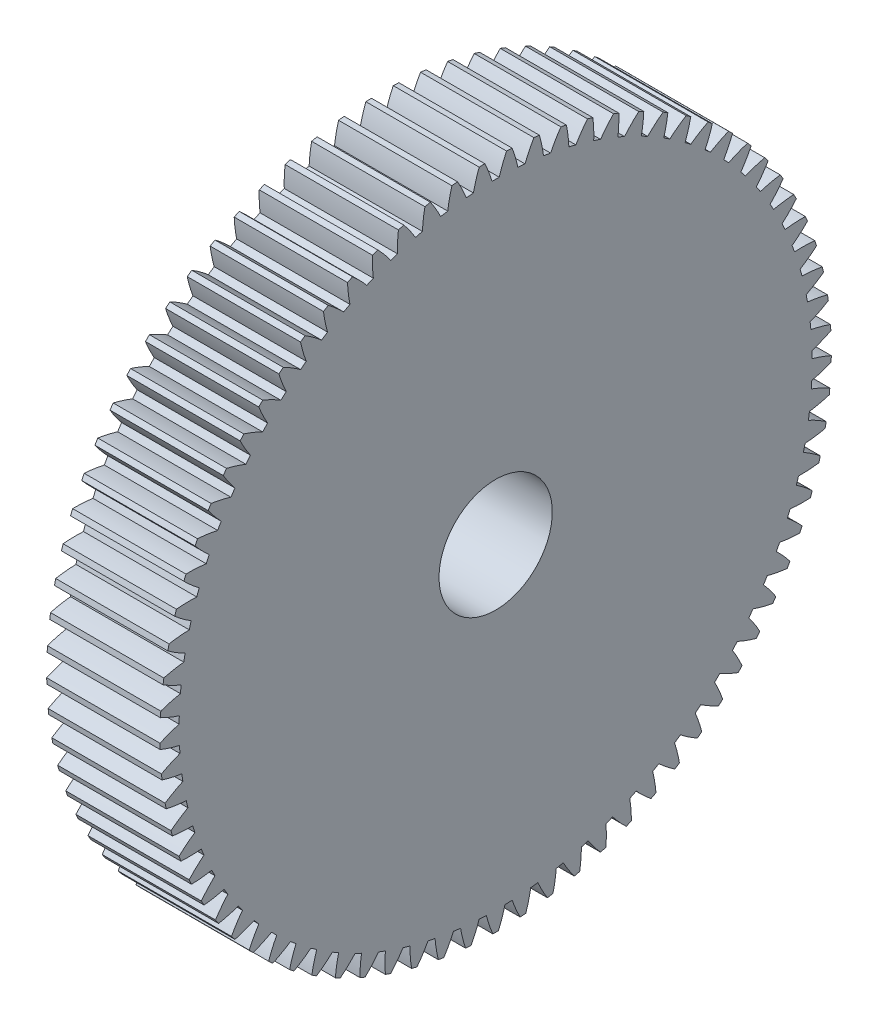
SolidWorks part; units mm, degrees
ref_plane "Plane1" through (0, 0, 0) normal (0, 0, 1) x (1, 0, 0)
ref_plane "Plane2" through (0, 0, 0) normal (0, 1, 0) x (1, 0, 0)
ref_plane "Plane3" through (0, 0, 0) normal (1, 0, 0) x (0, 0, -1)
sketch "HoldingSke" plane through (0, 0, 0) normal (0, 1, 0) x (1, 0, 0)
  line L0 (0, 0) -> (0.3749, -1.624)
  line L1 (-15, 0) -> (100, 0) construction
  line L2 (0, 0) -> (-2.1039, 2.3779)
  line L3 (0, 0) -> (-11.863, 4.5341)
  line L4 (0, 0) -> (1.9427, 8.4147)
  line L5 (0, 0) -> (-46.8476, -17.4728)
  line L6 (0, 0) -> (-6.6317, -4.4744)
  line L7 (-2.1039, 2.3779) -> (8.6586, 51.2059)
  line L8 (-76.2, 54.61) -> (-75.2, 54.61)
  line L9 (-71.009, 38.7566) -> (-53.1078, 45.2721)
  line L10 (-76.2, 71.12) -> (104.1128, 71.12)
  line L11 (0, 0) -> (-8, 0)
  line L12 (-76.2, 101.6) -> (-76.177, 101.6)
  line L13 (24.9733, 27.94) -> (52.9518, 28.4284)
  line L14 (24.9733, 27.94) -> (24.9743, 27.94)
  line L15 (24.9733, 27.94) -> (100.4006, 29.5858)
  line L16 (-63.627, -0.6) -> (-12.827, -0.6)
  circle A0 centre (0, 0) radius 4
  circle A1 centre (0, 0) radius 22.349
  circle A2 centre (0, 0) radius 37.5
  circle A3 centre (0, 0) radius 4
  dimension "MHD" = 44.698
  dimension "Hub_dia" = 75
  dimension "Bore" = 8
  dimension "MBD" = 8
  dimension "Num_teeth" = 77
  dimension "Pitch" = 1.6667
  dimension "Overall_len" = 50
  dimension "Show_teeth" = 77
  dimension "Thickness" = 8
  dimension "OAL" = 50.0001
  dimension "T_dim" = 1
  dimension "Ap" = 20
  dimension "H" = 19.05
  dimension "Pitch_radius" = 180.3128
  dimension "Width" = 8
  dimension "Backlash" = 0.023
  dimension "Addendum_fac" = 1
  dimension "Dedendum_fac" = 1.25
  dimension "Clearance_fac" = 0.25
  dimension "Dedendum_add" = 0.001
  dimension "Module" = 0.6
sketch "BasProSke" plane through (0, 0, 0) normal (0, 1, 0) x (1, 0, 0)
  line L0 (-10, 0) -> (60, 0) construction
  line L1 (0, 0) -> (0, 23.7)
  line L2 (0, 0) -> (8, 0)
  line L3 (8, 0) -> (8, 23.7)
  line L4 (8, 23.7) -> (0, 23.7)
  dimension "Thickness" = 8
  dimension "Diameter" = 47.4
revolve "Base-Revolve" add sketch "BasProSke" angle 360 about L0
sketch "TooCutSke" plane through (0, 0, 0) normal (1, 0, 0) x (0, 0, -1)
  line L1 (0, 0) -> (0, 107) construction
  line L2 (0, 0) -> (-0.5115, 23.0943) construction
  line L3 (0, 0) -> (-1.8841, 46.1535) construction
  line L4 (-0.5115, 23.0943) -> (-0.9421, 23.0768) construction
  arc A0 (0.2532, 22.3476) -> (-0.2532, 22.3476) centre (0, 0) ccw
  arc A1 (0.7818, 23.7125) -> (-0.7818, 23.7125) centre (0, 0) ccw
  circle A2 centre (0, 0) radius 23.1 construction
  circle A3 centre (0, 0) radius 21.7069 construction
  arc A4 (-0.2532, 22.3476) -> (-0.7818, 23.7125) centre (-9.107, 19.7041) ccw
  arc A5 (0.7818, 23.7125) -> (0.2532, 22.3476) centre (9.107, 19.7041) ccw
  dimension "Root_dia" = 44.698
  dimension "Overcut_dia" = 47.4508
  dimension "Pitch_dia" = 46.2
  dimension "Base_dia" = 43.4138
  dimension "Flank_rad" = 9.24
  dimension "Half_ang" = 2.338
  dimension "Half_CT" = 0.431
extrude "ToothCut" cut sketch "TooCutSke" along normal through all
fillet "Breaks" [suppressed] radius 0.012
fillet "RootFillets" [suppressed] radius 0.151
pattern_circular "TeethCuts" count 77 every 4.675 about axis through (-10, 0, 0) along (1, 0, 0) of "ToothCut", "RootFillets", "Breaks"
sketch "HubNeaOneSke" plane through (0, 0, 0) normal (-1, 0, 0) x (0, 0, 1)
  circle A0 centre (0, 0) radius 22.349
  dimension "Diameter" = 44.698
extrude "HubNearOne" [suppressed] add sketch "HubNeaOneSke" along normal blind 42.0001
sketch "HubNeaBotSke" plane through (0, 0, 0) normal (-1, 0, 0) x (0, 0, 1)
  circle A0 centre (0, 0) radius 22.349
  dimension "Diameter" = 44.698
extrude "HubNearBoth" [suppressed] add sketch "HubNeaBotSke" along normal blind 21
ref_plane "FarPln" through (8, 0, 0) normal (1, 0, 0) x (0, 0, -1)
sketch "HubFarSke" plane through (8, 0, 0) normal (1, 0, 0) x (0, 0, -1)
  circle A0 centre (0, 0) radius 22.349
  dimension "Diameter" = 44.698
extrude "HubFar" [suppressed] add sketch "HubFarSke" along normal blind 21
sketch "BorSke" plane through (0, 0, 0) normal (1, 0, 0) x (0, 0, -1)
  circle A0 centre (0, 0) radius 4
  dimension "Diameter" = 8
extrude "Bore" cut sketch "BorSke" along normal mid plane 100.0001
sketch "KeySke" plane through (0, 0, 0) normal (1, 0, 0) x (0, 0, -1)
  line L0 (-1, 0) -> (-1, 5)
  line L1 (-1, 5) -> (1, 5)
  line L2 (1, 5) -> (1, 0)
  line L3 (0, 0) -> (0, 34) construction
  line L4 (-1, 0) -> (1, 0)
  dimension "Offset" = 5
  dimension "Width" = 2
extrude "Keyway" [suppressed] cut sketch "KeySke" along normal mid plane 100.0001
pattern_circular "Keyway2" [suppressed] count 2 every 90 about axis through (-10, 0, 0) along (1, 0, 0)
equation "' \"Module@HoldingSke\" = 6.35"
equation "' \"Num_teeth@HoldingSke\" = 12"
equation "' \"Ap@HoldingSke\" =  20"
equation "' \"Ap@HoldingSke\" = 20"
equation "' \"Width@HoldingSke\" = 0.5 * 25.4"
equation "' \"Hub_dia@HoldingSke\"= 1 * 25.4"
equation "' \"Hub_dia@HoldingSke\" = 1 * 25.4"
equation "' \"Overall_len@HoldingSke\" = 1.0 * 25.4"
equation "' \"Bore@HoldingSke\" = 0.75 * 25.4"
equation "' \"T_dim@HoldingSke\" = 0.1 * 25.4"
equation "' \"Width@KeySke\" = 0.25 * 25.4"
equation "' \"Show_teeth@HoldingSke\" = 13"
equation "' \"Backlash@HoldingSke\" = 0.009 * 25.4"
equation "' \"Addendum_fac@HoldingSke\" = 1.0"
equation "' \"Dedendum_fac@HoldingSke\" = 1.25"
equation "' \"Dedendum_add@HoldingSke\" = 0.00005 * 25.4"
equation "' \"Clearance_fac@HoldingSke\" = 0.25"
equation "\"Pitch@HoldingSke\" = 1 / \"Module@HoldingSke\""
equation "\"Overcut_dia@TooCutSke\" = (\"Num_teeth@HoldingSke\" + 2 * \"Addendum_fac@HoldingSke\") / \"Pitch@HoldingSke\" + 0.002 * 25.4"
equation "\"Pitch_dia@TooCutSke\" = \"Num_teeth@HoldingSke\" / \"Pitch@HoldingSke\""
equation "\"Base_dia@TooCutSke\" = \"Num_teeth@HoldingSke\" / \"Pitch@HoldingSke\" * cos((\"Ap@HoldingSke\"  * 3.14159265 / 180))"
equation "\"Root_dia@TooCutSke\" = (\"Num_teeth@HoldingSke\" + 2) / \"Pitch@HoldingSke\" - 2 * (\"Addendum_fac@HoldingSke\" + \"Dedendum_fac@HoldingSke\") / \"Pitch@HoldingSke\" - \"Dedendum_add@HoldingSke\" * 2"
equation "\"Half_ang@TooCutSke\" = 180 / \"Num_teeth@HoldingSke\""
equation "\"Half_CT@TooCutSke\" = \"Num_teeth@HoldingSke\" / \"Pitch@HoldingSke\" * sin((3.14159265 / 2 / \"Num_teeth@HoldingSke\")) / 2 - 7 * \"Backlash@HoldingSke\" / 4"
equation "\"Flank_rad@TooCutSke\" = \"Num_teeth@HoldingSke\" / \"Pitch@HoldingSke\" / 5"
equation "\"Radius@RootFillets\" = \"Clearance_fac@HoldingSke\" / \"Pitch@HoldingSke\" + \"Dedendum_add@HoldingSke\""
equation "\"Break_rad@Breaks\" = 0.02 / \"Pitch@HoldingSke\""
equation "\"Thickness@HoldingSke\" = \"Width@HoldingSke\""
equation "\"OAL@HoldingSke\" = \"Thickness@HoldingSke\""
equation "\"MHD@HoldingSke\" = (\"Num_teeth@HoldingSke\" + 2) / \"Pitch@HoldingSke\" - 2 * (\"Addendum_fac@HoldingSke\" + \"Dedendum_fac@HoldingSke\")  / \"Pitch@HoldingSke\" - \"Dedendum_add@HoldingSke\" * 2"
equation "\"MBD@HoldingSke\" = (\"Num_teeth@HoldingSke\" + 2) / \"Pitch@HoldingSke\" - 2 * (\"Addendum_fac@HoldingSke\" + \"Dedendum_fac@HoldingSke\")  / \"Pitch@HoldingSke\" - \"Dedendum_add@HoldingSke\" * 2 - 0.002 * 25.4"
equation "\"MHD@HoldingSke\" = ((sgn( \"MHD@HoldingSke\" - \"Hub_dia@HoldingSke\" )-1)*( \"MHD@HoldingSke\" - \"Hub_dia@HoldingSke\" ))/-2+ \"Hub_dia@HoldingSke\""
equation "\"MBD@HoldingSke\" = ((sgn( \"MBD@HoldingSke\" - \"Bore@HoldingSke\" )-1)*( \"MBD@HoldingSke\" - \"Bore@HoldingSke\" ))/-2+ \"Bore@HoldingSke\""
equation "\"OAL@HoldingSke\" = ((sgn( \"OAL@HoldingSke\" - \"Overall_len@HoldingSke\" )+1)*( \"OAL@HoldingSke\" - \"Overall_len@HoldingSke\" ))/2 + \"Overall_len@HoldingSke\" + 0.000002 * 25.4"
equation "\"Num_teeth@TeethCuts\" = int( \"Show_teeth@HoldingSke\" ) + 1"
equation "\"Num_teeth@TeethCuts\" = ((sgn( \"Num_teeth@TeethCuts\" - \"Num_teeth@HoldingSke\" )-1)*( \"Num_teeth@TeethCuts\" - \"Num_teeth@HoldingSke\" ))/-2+ \"Num_teeth@HoldingSke\""
equation "\"Num_teeth@TeethCuts\" = ((sgn( \"Num_teeth@TeethCuts\" - 2.0)+1)*( \"Num_teeth@TeethCuts\" - 2.0))/2 +2.0"
equation "\"Angle@TeethCuts\" = 360.0 / \"Num_teeth@HoldingSke\""
equation "\"Diameter@BasProSke\" = (\"Num_teeth@HoldingSke\" + 2 * \"Addendum_fac@HoldingSke\") / \"Pitch@HoldingSke\""
equation "\"Thickness@BasProSke\"  = \"Thickness@HoldingSke\""
equation "' \"Fillet_rad@BasProSke\" =  \"Thickness@HoldingSke\" * 0.05"
equation "' \"Fillet_rad@BasProSke\" = \"Thickness@HoldingSke\" * 0.05"
equation "\"MHD@HoldingSke\" = ((sgn( \"MHD@HoldingSke\" - \"Root_dia@TooCutSke\" )-1)*( \"MHD@HoldingSke\" - \"Root_dia@TooCutSke\" ))/-2+ \"Root_dia@TooCutSke\""
equation "\"Diameter@HubNeaOneSke\" = \"MHD@HoldingSke\""
equation "\"Length@HubNearOne\" = \"OAL@HoldingSke\" - \"Thickness@BasProSke\""
equation "\"Diameter@HubNeaBotSke\" = \"MHD@HoldingSke\""
equation "\"Length@HubNearBoth\" = ( \"OAL@HoldingSke\" - \"Thickness@BasProSke\" ) / 2.0"
equation "\"Thickness@FarPln\" = \"Thickness@BasProSke\""
equation "\"Diameter@HubFarSke\" = \"MHD@HoldingSke\""
equation "\"Length@HubFar\" = ( \"OAL@HoldingSke\" - \"Thickness@BasProSke\" ) / 2.0"
equation "\"Diameter@BorSke\" = \"MBD@HoldingSke\""
equation "\"D1@Bore\" = \"OAL@HoldingSke\" * 2.0"
equation "\"D1@Keyway\" = \"OAL@HoldingSke\" * 2.0"
equation "\"Offset@KeySke\" = \"T_dim@HoldingSke\" + \"MBD@HoldingSke\" / 2.0"
